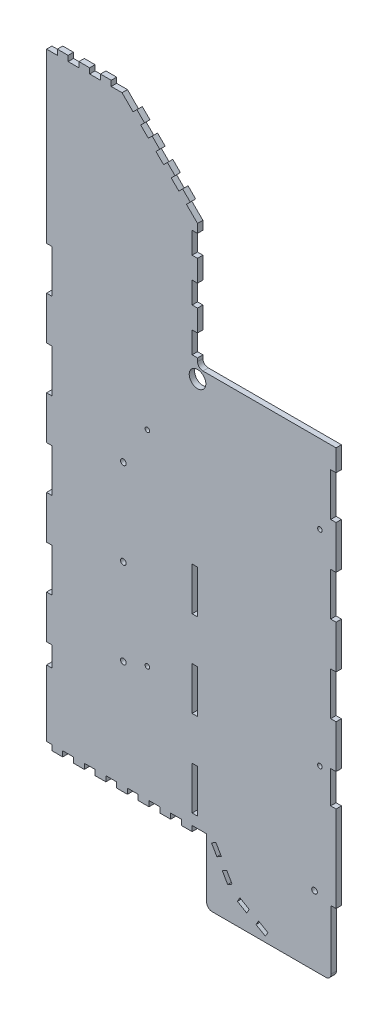
SolidWorks part; units mm, degrees
material "Acrylic (Medium-high impact)"
ref_plane "Front Plane" through (0, 0, 0) normal (0, 0, 1) x (1, 0, 0)
ref_plane "Top Plane" through (0, 0, 0) normal (0, 1, 0) x (1, 0, 0)
ref_plane "Right Plane" through (0, 0, 0) normal (1, 0, 0) x (0, 0, -1)
sketch "Sketch1" plane through (0, 0, 0) normal (0, 0, 1) x (1, 0, 0)
  line L0 (0, 3.175) -> (3.175, 3.175)
  line L1 (3.175, 3.175) -> (3.175, 0)
  line L2 (3.175, 0) -> (9.525, 0)
  line L3 (9.525, 0) -> (9.525, 3.175)
  line L4 (9.525, 3.175) -> (15.875, 3.175)
  line L5 (15.875, 3.175) -> (15.875, 0)
  line L6 (15.875, 0) -> (22.225, 0)
  line L7 (22.225, 0) -> (22.225, 3.175)
  line L8 (22.225, 3.175) -> (28.575, 3.175)
  line L9 (28.575, 3.175) -> (28.575, 0)
  line L10 (28.575, 0) -> (34.925, 0)
  line L11 (34.925, 0) -> (34.925, 3.175)
  line L12 (34.925, 3.175) -> (41.275, 3.175)
  line L13 (41.275, 3.175) -> (41.275, 0)
  line L14 (41.275, 0) -> (47.625, 0)
  line L15 (47.625, 0) -> (47.625, 3.175)
  line L16 (47.625, 3.175) -> (53.975, 3.175)
  line L17 (53.975, 3.175) -> (53.975, 0)
  line L18 (53.975, 0) -> (60.325, 0)
  line L19 (60.325, 0) -> (60.325, 3.175)
  line L20 (60.325, 3.175) -> (66.675, 3.175)
  line L21 (66.675, 3.175) -> (66.675, 0)
  line L22 (66.675, 0) -> (73.025, 0)
  line L23 (73.025, 0) -> (73.025, 3.175)
  line L24 (73.025, 3.175) -> (79.375, 3.175)
  line L25 (79.375, 3.175) -> (79.375, 0)
  line L26 (79.375, 0) -> (85.725, 0)
  line L27 (85.725, 0) -> (85.725, 3.175)
  line L28 (85.725, 3.175) -> (88.9, 3.175)
  line L29 (0, 3.175) -> (0, 28.575)
  line L30 (0, 356.235) -> (6.35, 356.235)
  line L31 (88.9, 238.125) -> (88.9, 243.205)
  line L32 (0, 28.575) -> (3.175, 28.575) construction
  line L33 (3.175, 28.575) -> (3.175, 42.175) construction
  line L34 (3.175, 53.975) -> (0, 53.975)
  line L35 (0, 79.375) -> (3.175, 79.375)
  line L36 (3.175, 79.375) -> (3.175, 104.775)
  line L37 (3.175, 104.775) -> (0, 104.775)
  line L38 (0, 130.175) -> (3.175, 130.175)
  line L39 (3.175, 130.175) -> (3.175, 155.575)
  line L40 (3.175, 155.575) -> (0, 155.575)
  line L41 (0, 180.975) -> (3.175, 180.975)
  line L42 (3.175, 180.975) -> (3.175, 206.375)
  line L43 (3.175, 206.375) -> (0, 206.375)
  line L44 (0, 231.775) -> (3.175, 231.775)
  line L45 (3.175, 231.775) -> (3.175, 257.175)
  line L46 (3.175, 257.175) -> (0, 257.175)
  line L47 (0, 257.175) -> (0, 356.235)
  line L48 (0, 206.375) -> (0, 231.775)
  line L49 (0, 155.575) -> (0, 180.975)
  line L50 (0, 104.775) -> (0, 130.175)
  line L51 (0, 53.975) -> (0, 79.375)
  line L52 (44.45, 356.235) -> (50.9596, 349.7254)
  line L53 (88.9, 20.278) -> (120.7715, -34.925) construction
  line L54 (85.725, 111.125) -> (88.9, 111.125)
  line L55 (85.725, 111.125) -> (85.725, 136.525)
  line L56 (85.725, 136.525) -> (88.9, 136.525)
  line L57 (88.9, 111.125) -> (88.9, 136.525)
  line L58 (110.9837, -17.9721) -> (140.347, -34.925) construction
  line L59 (99.7423, 1.4986) -> (102.9173, -4.0007)
  line L60 (102.9173, -4.0007) -> (100.3217, -5.4993)
  line L61 (170.4848, 225.425) -> (167.3098, 225.425)
  line L62 (85.725, 85.725) -> (88.9, 85.725)
  line L63 (85.725, 85.725) -> (85.725, 60.325)
  line L64 (85.725, 60.325) -> (88.9, 60.325)
  line L65 (88.9, 85.725) -> (88.9, 60.325)
  line L66 (85.725, 34.925) -> (88.9, 34.925)
  line L67 (85.725, 34.925) -> (85.725, 9.525)
  line L68 (85.725, 9.525) -> (88.9, 9.525)
  line L69 (88.9, 34.925) -> (88.9, 9.525)
  line L70 (167.3098, 225.425) -> (167.3098, 200.025)
  line L71 (167.3098, 200.025) -> (170.4848, 200.025)
  line L72 (170.4848, 174.625) -> (167.3098, 174.625)
  line L73 (167.3098, 174.625) -> (167.3098, 149.225)
  line L74 (167.3098, 149.225) -> (170.4848, 149.225)
  line L75 (170.4848, 123.825) -> (167.3098, 123.825)
  line L76 (167.3098, 123.825) -> (167.3098, 98.425)
  line L77 (167.3098, 98.425) -> (170.4848, 98.425)
  line L78 (170.4848, 225.425) -> (170.4848, 238.125)
  line L79 (170.4848, 174.625) -> (170.4848, 200.025)
  line L80 (88.9, 3.175) -> (94.2848, 3.175)
  line L81 (170.4848, 3.175) -> (170.4848, 53.975)
  line L82 (170.4848, 238.125) -> (88.9, 238.125)
  line L83 (170.4848, 3.175) -> (170.4848, -34.925) construction
  line L84 (170.4848, -34.925) -> (167.5356, -34.925) construction
  line L85 (94.2848, -34.925) -> (94.2848, 3.175)
  line L86 (88.9, 311.785) -> (0, 311.785) construction
  line L87 (6.35, 356.235) -> (6.35, 359.41)
  line L88 (6.35, 359.41) -> (12.7, 359.41)
  line L89 (12.7, 359.41) -> (12.7, 356.235)
  line L90 (19.05, 356.235) -> (19.05, 359.41)
  line L91 (19.05, 359.41) -> (25.4, 359.41)
  line L92 (25.4, 359.41) -> (25.4, 356.235)
  line L93 (12.7, 356.235) -> (19.05, 356.235)
  line L94 (25.4, 356.235) -> (31.75, 356.235)
  line L95 (31.75, 356.235) -> (31.75, 359.41)
  line L96 (31.75, 359.41) -> (38.1, 359.41)
  line L97 (38.1, 359.41) -> (38.1, 356.235)
  line L98 (38.1, 356.235) -> (44.45, 356.235)
  line L99 (50.9596, 349.7254) -> (53.2046, 351.9705)
  line L100 (53.2046, 351.9705) -> (57.6947, 347.4804)
  line L101 (57.6947, 347.4804) -> (55.4497, 345.2353)
  line L102 (59.9398, 340.7452) -> (62.1849, 342.9903)
  line L103 (62.1849, 342.9903) -> (66.675, 338.5001)
  line L104 (66.675, 338.5001) -> (64.4299, 336.2551)
  line L105 (68.9201, 331.7649) -> (71.1651, 334.01)
  line L106 (71.1651, 334.01) -> (75.6553, 329.5199)
  line L107 (75.6553, 329.5199) -> (73.4102, 327.2748)
  line L108 (77.9003, 322.7847) -> (80.1454, 325.0297)
  line L109 (80.1454, 325.0297) -> (84.6355, 320.5396)
  line L110 (84.6355, 320.5396) -> (82.3904, 318.2946)
  line L111 (55.4497, 345.2353) -> (59.9398, 340.7452)
  line L112 (64.4299, 336.2551) -> (68.9201, 331.7649)
  line L113 (73.4102, 327.2748) -> (77.9003, 322.7847)
  line L114 (82.3904, 318.2946) -> (88.9, 311.785)
  line L115 (170.4848, 123.825) -> (170.4848, 149.225)
  line L116 (0, 28.575) -> (0, 42.175)
  line L117 (0, 42.175) -> (3.175, 42.175)
  line L118 (3.175, 42.175) -> (3.175, 53.975)
  line L119 (100.3217, -5.4993) -> (97.1467, 0)
  line L120 (97.1467, 0) -> (99.7423, 1.4986)
  line L121 (106.0923, -9.4999) -> (103.4967, -10.9985)
  line L122 (103.4967, -10.9985) -> (106.6717, -16.4978)
  line L123 (106.6717, -16.4978) -> (109.2673, -14.9992)
  line L124 (106.0923, -9.4999) -> (109.2673, -14.9992)
  line L125 (113.8542, -19.6293) -> (112.3556, -22.225)
  line L126 (112.3556, -22.225) -> (117.8548, -25.4)
  line L127 (117.8548, -25.4) -> (119.3534, -22.8043)
  line L128 (113.8542, -19.6293) -> (119.3534, -22.8043)
  line L129 (124.8527, -25.9793) -> (123.3541, -28.575)
  line L130 (123.3541, -28.575) -> (128.8534, -31.75)
  line L131 (128.8534, -31.75) -> (130.352, -29.1543)
  line L132 (130.352, -29.1543) -> (124.8527, -25.9793)
  line L133 (170.4848, 73.025) -> (167.3098, 73.025)
  line L134 (167.3098, 73.025) -> (167.3098, 53.975)
  line L135 (167.3098, 53.975) -> (170.4848, 53.975)
  line L136 (170.4848, 73.025) -> (170.4848, 98.425)
  line L137 (88.9, 306.705) -> (85.725, 306.705)
  line L138 (85.725, 306.705) -> (85.725, 294.005)
  line L139 (85.725, 294.005) -> (88.9, 294.005)
  line L140 (88.9, 281.305) -> (85.725, 281.305)
  line L141 (85.725, 281.305) -> (85.725, 268.605)
  line L142 (85.725, 268.605) -> (88.9, 268.605)
  line L143 (88.9, 255.905) -> (85.725, 255.905)
  line L144 (85.725, 255.905) -> (85.725, 243.205)
  line L145 (85.725, 243.205) -> (88.9, 243.205)
  line L146 (88.9, 306.705) -> (88.9, 311.785)
  line L147 (88.9, 281.305) -> (88.9, 294.005)
  line L148 (88.9, 255.905) -> (88.9, 268.605)
  line L149 (167.5356, -34.925) -> (167.5356, 3.175)
  line L150 (167.5356, 3.175) -> (170.4848, 3.175)
  line L151 (167.5356, -34.925) -> (94.2848, -34.925)
  circle A0 centre (88.9, 232.41) radius 4.8895
  circle A1 centre (59.3598, 191.77) radius 1.3335
  circle A2 centre (59.3598, 71.12) radius 1.3335
  circle A3 centre (160.9598, 71.12) radius 1.3335
  circle A4 centre (160.9598, 191.77) radius 1.3335
  circle A5 centre (157.7848, 5.969) radius 2.794 construction
  circle A6 centre (45.225, 66.575) radius 1.651
  circle A7 centre (45.225, 117.375) radius 1.651
  circle A8 centre (45.225, 168.175) radius 1.651
  circle A9 centre (157.7848, 5.969) radius 1.651
  point P61 (170.4848, 41.529)
  dimension "D13" = 9.779
  dimension "D20" = 2.667
  dimension "D34" = 76.454
  dimension "D36" = 3.302
  dimension "D54" = 5.588
  dimension "D1" = 3.175
  dimension "D2" = 3.175
  dimension "D3" = 6.35
  dimension "D4" = 3.175
  dimension "D5" = 353.06
  dimension "D6" = 25.4
  dimension "D7" = 25.4
  dimension "D8" = 5
  dimension "D9" = 42.05
  dimension "D10" = 25.4
  dimension "D11" = 234.95
  dimension "D12" = 81.5848
  dimension "D14" = 5.715
  dimension "D15" = 38.1
  dimension "D16" = 76.2
  dimension "D17" = 44.45
  dimension "D18" = 45
  dimension "D19" = 4
  dimension "D21" = 101.6
  dimension "D22" = 120.65
  dimension "D24" = 6.35
  dimension "D25" = 25.4
  dimension "D26" = 25.4
  dimension "D27" = 6.35
  dimension "D28" = 25.4
  dimension "D29" = 3.175
  dimension "D30" = 25.4
  dimension "D31" = 12.7
  dimension "D33" = 25.4
  dimension "D23" = 40.64
  dimension "D35" = 63.4
  dimension "D37" = 40.5
  dimension "D39" = 50.8
  dimension "D40" = 39
  dimension "D41" = 30
  dimension "D42" = 81.28
  dimension "D43" = 30
  dimension "D44" = 81.28
  dimension "D45" = 2.9972
  dimension "D46" = 6.35
  dimension "D47" = 3.175
  dimension "D48" = 6.35
  dimension "D49" = 6.35
  dimension "D50" = 3.175
  dimension "D51" = 19.05
  dimension "D52" = 12.7
  dimension "D53" = 3.175
  dimension "D55" = 2.794
  dimension "D56" = 12.7
  dimension "D58" = 2.9492
  dimension "D32" = 3
  dimension "D38" = 3
extrude "Boss-Extrude2" add sketch "Sketch1" along normal blind 3.175
fillet "Fillet1" radius 3.175 3 edges at (88.9, 238.125, 1.5875) (94.2848, -34.925, 1.5875) (167.5356, -34.925, 1.5875)
